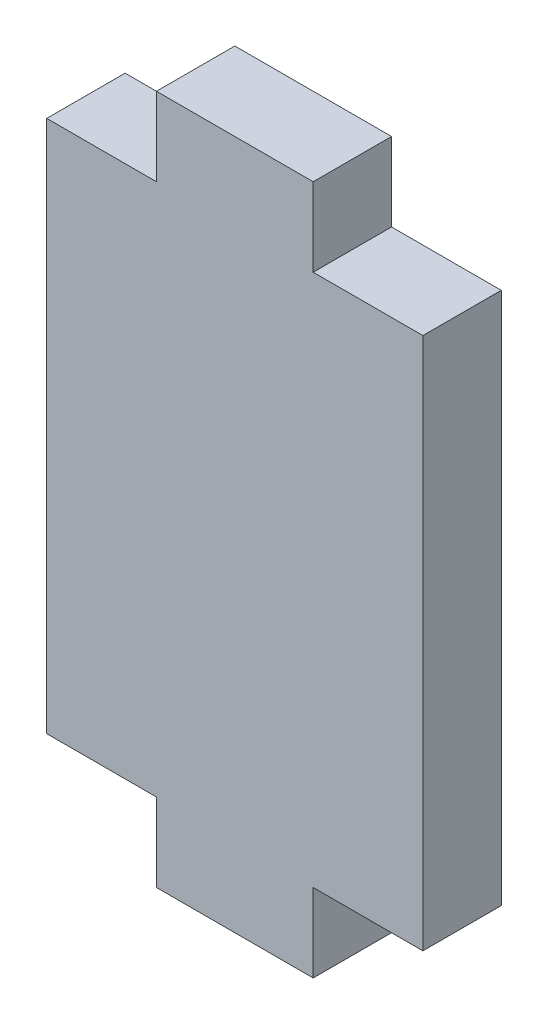
SolidWorks part; units mm, degrees
ref_plane "Front Plane" through (0, 0, 0) normal (0, 0, 1) x (1, 0, 0)
ref_plane "Top Plane" through (0, 0, 0) normal (0, 1, 0) x (1, 0, 0)
ref_plane "Right Plane" through (0, 0, 0) normal (1, 0, 0) x (0, 0, -1)
sketch "Sketch1" plane through (0, 0, 0) normal (0, 0, 1) x (1, 0, 0)
  line L1 (-24, 44) -> (24, 44)
  line L2 (-24, 44) -> (-24, -44)
  line L3 (-24, -44) -> (24, -44)
  line L4 (24, 44) -> (24, -44)
  line L5 (-24, 44) -> (24, -44) construction
  line L6 (-24, -44) -> (24, 44) construction
  point P0 (0, 0)
  dimension "D1" = 48
  dimension "D2" = 88
extrude "Boss-Extrude1" add sketch "Sketch1" along normal blind 10
sketch "Sketch2" plane through (0, 0, 10) normal (0, 0, 1) x (1, 0, 0)
  line L0 (-24, 0) -> (24, 0) construction
  line L5 (-24, 44) -> (-18.5455, 34) construction
  line L6 (-24, 44) -> (-24, -44) construction
  line L7 (-38, 54) -> (-10, 54)
  line L8 (-38, 54) -> (-38, 34)
  line L9 (-38, 34) -> (-10, 34)
  line L10 (-10, 54) -> (-10, 34)
  line L11 (-38, 54) -> (-10, 34) construction
  line L12 (-38, 34) -> (-10, 54) construction
  line L17 (24, -44) -> (24, 44) construction
  line L18 (0, 44) -> (0, -44) construction
  line L19 (24, 44) -> (-24, 44) construction
  line L20 (-24, -44) -> (24, -44) construction
  line L21 (38, 34) -> (10, 54) construction
  line L22 (38, 54) -> (10, 34) construction
  line L23 (24, 44) -> (18.5455, 34) construction
  line L24 (10, 54) -> (10, 34)
  line L25 (38, 34) -> (10, 34)
  line L26 (38, 54) -> (38, 34)
  line L27 (38, 54) -> (10, 54)
  line L28 (38, -54) -> (10, -54)
  line L29 (10, -54) -> (10, -34)
  line L30 (24, -44) -> (18.5455, -34) construction
  line L31 (38, -54) -> (10, -34) construction
  line L32 (38, -34) -> (10, -54) construction
  line L33 (38, -54) -> (38, -34)
  line L34 (38, -34) -> (10, -34)
  line L35 (-38, -34) -> (-10, -54) construction
  line L36 (-38, -54) -> (-10, -34) construction
  line L37 (-24, -44) -> (-18.5455, -34) construction
  line L38 (-10, -54) -> (-10, -34)
  line L39 (-38, -34) -> (-10, -34)
  line L40 (-38, -54) -> (-38, -34)
  line L41 (-38, -54) -> (-10, -54)
  point P0 (0, 0)
  dimension "D1" = 20
  dimension "D2" = 28
  dimension "D3" = 20
extrude "Cut-Extrude1" cut sketch "Sketch2" against normal blind 10
